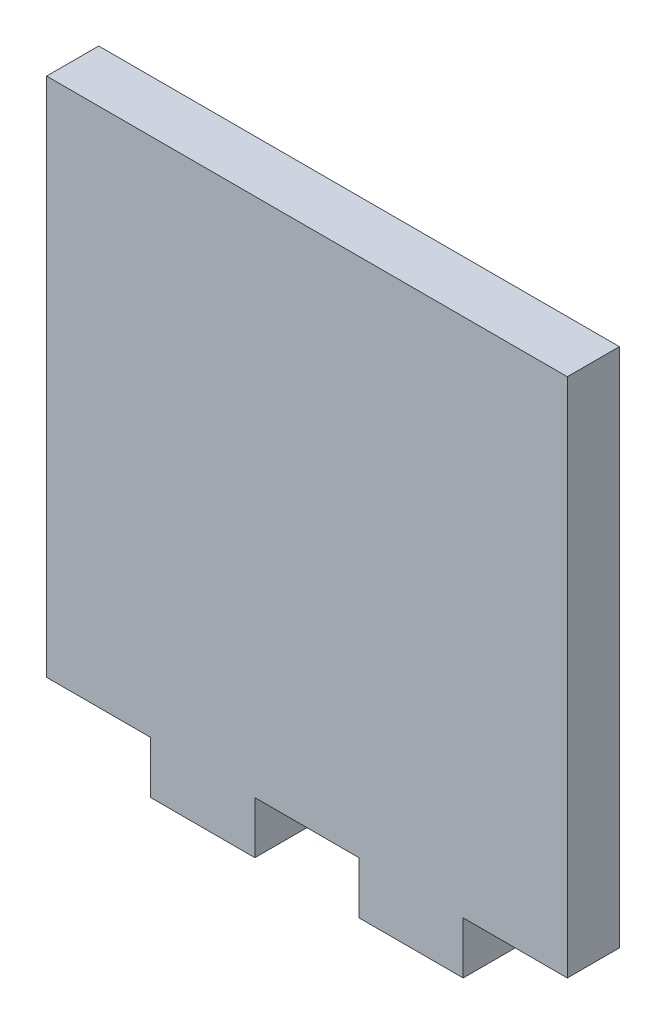
SolidWorks part; units mm, degrees
ref_plane "Plan de face" through (0, 0, 0) normal (0, 0, 1) x (1, 0, 0)
ref_plane "Plan de dessus" through (0, 0, 0) normal (0, 1, 0) x (1, 0, 0)
ref_plane "Plan de droite" through (0, 0, 0) normal (1, 0, 0) x (0, 0, -1)
sketch "Esquisse1" plane through (0, 0, 0) normal (0, 0, 1) x (1, 0, 0)
  line L0 (-7.5744, 0) -> (2.4256, 0)
  line L1 (-7.5744, 50) -> (42.4256, 50)
  line L5 (2.4256, 0) -> (2.4256, -5)
  line L6 (2.4256, -5) -> (12.4256, -5)
  line L7 (12.4256, -5) -> (12.4256, 0)
  line L8 (12.4256, 0) -> (22.4256, 0)
  line L9 (22.4256, 0) -> (22.4256, -5)
  line L10 (22.4256, -5) -> (32.4256, -5)
  line L11 (32.4256, -5) -> (32.4256, 0)
  line L12 (32.4256, 0) -> (42.4256, 0)
  line L13 (42.4256, 50) -> (42.4256, 0)
  line L14 (-7.5744, 50) -> (-7.5744, 0)
  point P6 (32.4256, -2.5)
  dimension "D1" = 5
  dimension "D2" = 5
  dimension "D3" = 10
  dimension "D4" = 10
  dimension "D5" = 50
  dimension "D6" = 10
extrude "Boss.-Extru.1" add sketch "Esquisse1" along normal blind 5
